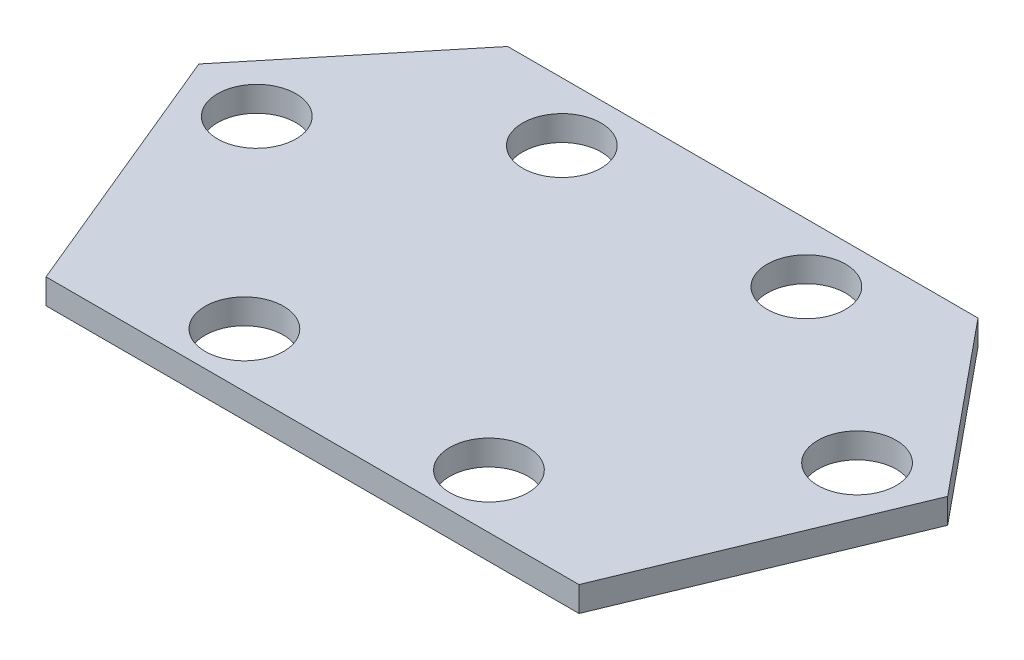
SolidWorks part; units mm, degrees
ref_plane "前视基准面" through (0, 0, 0) normal (0, 0, 1) x (1, 0, 0)
ref_plane "上视基准面" through (0, 0, 0) normal (0, 1, 0) x (1, 0, 0)
ref_plane "右视基准面" through (0, 0, 0) normal (1, 0, 0) x (0, 0, -1)
other "Configuration Table"
sketch "草图1" plane through (0, 0, 0) normal (0, 1, 0) x (1, 0, 0)
  line L0 (-75, 99.7097) -> (75, 99.7097)
  line L1 (75, 99.7097) -> (119.4207, 45.6098)
  line L2 (119.4207, 45.6098) -> (85, -37.548)
  line L3 (0, 10.8861) -> (0, -17.0004) construction
  line L4 (85, -37.548) -> (-85, -37.548)
  line L5 (-119.4207, 45.6098) -> (-85, -37.548)
  line L6 (-75, 99.7097) -> (-119.4207, 45.6098)
  line L7 (0, 184.4528) -> (0, -209.7421) construction
  circle A0 centre (-95.73, 40.3985) radius 12.5
  circle A1 centre (-39, 80.972) radius 12.5
  circle A2 centre (-39, -20.2755) radius 12.5
  circle A4 centre (39, -20.2755) radius 12.5
  circle A5 centre (39, 80.972) radius 12.5
  circle A6 centre (95.73, 40.3985) radius 12.5
  point P8 (0, -37.548)
  point P11 (0, 99.7097)
  dimension "D5" = 25
  dimension "D1" = 150
  dimension "D2" = 70
  dimension "D3" = 90
  dimension "D4" = 170
  dimension "D6" = 78
  dimension "D7" = 78
extrude "凸台-拉伸1" add sketch "草图1" along normal mid plane 8
